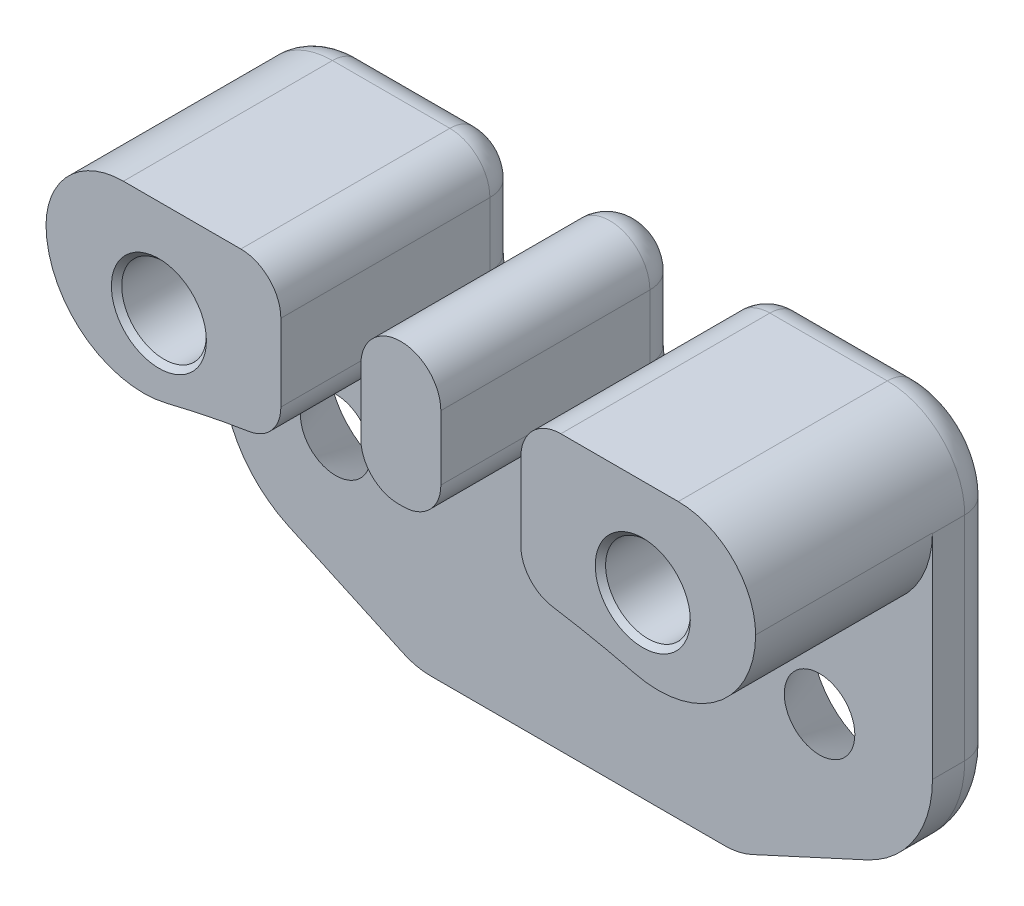
SolidWorks part; units mm, degrees
material "6061-T6 (SS)"
ref_plane "Front" through (0, 0, 0) normal (0, 0, 1) x (1, 0, 0)
ref_plane "Top" through (0, 0, 0) normal (0, 1, 0) x (1, 0, 0)
ref_plane "Right" through (0, 0, 0) normal (1, 0, 0) x (0, 0, -1)
sketch "Sketch1" plane through (0, 0, 0) normal (0, 0, 1) x (1, 0, 0)
  line L1 (0, 0) -> (-69.85, 0)
  line L2 (0, 0) -> (0, 44.45)
  line L3 (0, 44.45) -> (-69.85, 44.45)
  line L4 (-69.85, 0) -> (-69.85, 44.45)
  circle A0 centre (-58.7375, 34.925) radius 4.1672
  circle A1 centre (-11.1125, 34.925) radius 4.1672
  dimension "D3" = 8.3344
  dimension "D1" = 44.45
  dimension "D2" = 69.85
  dimension "D4" = 11.1125
  dimension "D5" = 9.525
  dimension "D6" = 9.525
  dimension "D7" = 11.1125
extrude "Boss-Extrude1" add sketch "Sketch1" against normal blind 23.749
sketch "Sketch2" plane through (0, 0, 0) normal (0, 0, 1) x (1, 0, 0)
  line L0 (-69.85, 0) -> (0, 0) construction
  line L1 (-34.925, 44.45) -> (-34.925, 0) construction
  line L2 (0, 0) -> (0, 44.45) construction
  line L3 (-69.85, 36.9576) -> (-69.85, 0)
  line L4 (-69.85, 0) -> (-34.925, 0)
  line L5 (0, 44.45) -> (-69.85, 44.45) construction
  line L6 (-69.85, 44.45) -> (-69.85, 0) construction
  line L7 (0, 0) -> (0, 36.9576)
  line L8 (-34.925, 0) -> (0, 0)
  arc A0 (-69.85, 36.9576) -> (-57.9471, 27.6559) centre (-60.264, 36.9576) ccw
  arc A1 (-11.9029, 27.6559) -> (-57.9471, 27.6559) centre (-34.925, -64.77) ccw
  arc A2 (0, 36.9576) -> (-11.9029, 27.6559) centre (-9.586, 36.9576) cw
  point P10 (-34.925, 30.48)
  dimension "D2" = 190.5
  dimension "D3" = 19.1719
  dimension "D1" = 13.97
extrude "Cut-Extrude1" cut sketch "Sketch2" against normal blind 17.399
sketch "Sketch3" plane through (0, 0, 0) normal (0, 0, 1) x (1, 0, 0)
  line L3 (-69.85, 36.83) -> (-69.85, 0)
  line L4 (-69.85, 0) -> (0, 0)
  line L5 (0, 0) -> (0, 36.83)
  line L6 (-7.62, 44.45) -> (-62.23, 44.45)
  arc A0 (0, 36.83) -> (-7.62, 44.45) centre (-7.62, 36.83) ccw
  arc A1 (-69.85, 36.83) -> (-62.23, 44.45) centre (-62.23, 36.83) cw
  point P8 (0, 44.45)
  point P11 (-69.85, 44.45)
  dimension "D1" = 7.62
extrude "Cut-Extrude2" cut sketch "Sketch3" against normal up to surface (23.749 mm away) flip side to cut up to face at (-6.9453, 34.925, -23.749)
sketch "Sketch4" plane through (0, 0, -17.399) normal (0, 0, 1) x (1, 0, 0)
  line L0 (-69.85, 44.45) -> (0, 44.45)
  line L1 (-50.8, 0) -> (-19.05, 0)
  line L2 (-69.85, 0) -> (0, 0) construction
  line L3 (-19.05, 0) -> (-6.4739, 5.7769)
  line L5 (-34.925, 44.45) -> (-34.925, 0) construction
  line L6 (0, 44.45) -> (0, 15.875)
  line L8 (-69.85, 44.45) -> (-69.85, 15.875)
  line L9 (-7.62, 44.45) -> (-62.23, 44.45) construction
  line L10 (-69.85, 0) -> (0, 0) construction
  line L11 (-50.8, 0) -> (-63.3761, 5.7769)
  line L12 (-74.8365, 15.875) -> (5.7772, 15.875) construction
  line L13 (-58.7375, 34.925) -> (-58.7375, 15.875) construction
  line L14 (0, 0) -> (0, 36.83) construction
  circle A0 centre (-58.7375, 34.925) radius 4.1672 construction
  arc A1 (0, 15.875) -> (-6.4739, 5.7769) centre (-11.1125, 15.875) cw
  arc A3 (-69.85, 15.875) -> (-63.3761, 5.7769) centre (-58.7375, 15.875) ccw
  dimension "D2" = 15.875
  dimension "D1" = 19.05
extrude "Cut-Extrude3" cut sketch "Sketch4" against normal up to surface (6.35 mm away) flip side to cut up to face at (-6.9453, 34.925, -23.749)
sketch "Sketch5" plane through (0, 0, 0) normal (0, 0, 1) x (1, 0, 0)
  line L1 (-7.62, 44.45) -> (-62.23, 44.45) construction
  line L2 (-38.862, 40.513) -> (-38.862, 34.2208)
  line L3 (-30.988, 34.2208) -> (-30.988, 40.513)
  line L4 (-46.736, 34.2208) -> (-46.736, 40.513)
  line L5 (-50.673, 44.45) -> (-34.925, 44.45)
  line L6 (-23.114, 34.2208) -> (-23.114, 40.513)
  line L7 (-19.177, 44.45) -> (-34.925, 44.45)
  arc A0 (-30.988, 40.513) -> (-38.862, 40.513) centre (-34.925, 40.513) ccw
  arc A1 (-30.988, 34.2208) -> (-23.114, 34.2208) centre (-27.051, 34.2208) ccw
  arc A2 (-46.736, 34.2208) -> (-38.862, 34.2208) centre (-42.799, 34.2208) ccw
  arc A3 (-46.736, 40.513) -> (-50.673, 44.45) centre (-50.673, 40.513) ccw
  arc A4 (-19.177, 44.45) -> (-23.114, 40.513) centre (-19.177, 40.513) ccw
  line M2 (-7.62, 44.45) -> (-62.23, 44.45)
  dimension "D1" = 7.874
extrude "Cut-Extrude4" cut sketch "Sketch5" against normal through all contours A3 L4 A2 L2 A0 M2 | A4 A0 L3 A1 L6 M2
sketch "Sketch6" plane through (0, 0, -23.749) normal (0, 0, -1) x (-1, 0, 0)
  circle A0 centre (11.1125, 15.875) radius 7.1374
  circle A1 centre (58.7375, 15.875) radius 7.1374
  dimension "D1" = 14.2748
  dimension "D2" = 19.05
extrude "Cut-Extrude6" cut sketch "Sketch6" against normal up to next (6.35 mm away) draft 30
sketch "Sketch7" plane through (0, 0, -17.399) normal (0, 0, 1) x (1, 0, 0)
  line L0 (-46.736, 37.3669) -> (-46.736, 27.7882)
  line L1 (-46.736, 34.2208) -> (-46.736, 40.513) construction
  line L2 (-46.736, 37.3669) -> (-38.862, 37.3669)
  line L3 (-38.862, 40.513) -> (-38.862, 34.2208) construction
  line L4 (-38.862, 37.3669) -> (-38.862, 27.7882)
  line L5 (-38.862, 27.7882) -> (-46.736, 27.7882)
  line L6 (-34.925, 44.45) -> (-34.925, 22.2992) construction
  line L7 (-30.988, 27.7882) -> (-23.114, 27.7882)
  line L8 (-30.988, 37.3669) -> (-30.988, 27.7882)
  line L9 (-23.114, 37.3669) -> (-30.988, 37.3669)
  line L10 (-23.114, 37.3669) -> (-23.114, 27.7882)
  arc A0 (-30.988, 40.513) -> (-38.862, 40.513) centre (-34.925, 40.513) ccw construction
extrude "Cut-Extrude7" cut sketch "Sketch7" along normal through all
fillet "Fillet2" radius 3.683 4 edges at (-30.988, 30.3986, -8.6995) (-38.862, 30.3986, -8.6995) (-23.114, 29.7449, -8.6995) (-46.736, 29.7449, -8.6995)
chamfer "Chamfer1" distance 0.508 angle 45 4 edges at (-54.5703, 34.925, -23.749) (-6.9453, 34.925, -23.749) (-6.9453, 34.925, 0) (-54.5703, 34.925, 0)
fillet "Fillet3" radius 6.35 2 edges at (-50.8, 0, -20.574) (-19.05, 0, -20.574)
fillet "Fillet4" radius 3.175 22 edges at (-1.7574, 9.8775, -23.749) (-12.131, 3.1783, -23.749) (-19.0821, 0.1466, -23.749) (-34.925, 0, -23.749) (-50.7679, 0.1466, -23.749) (-57.719, 3.1783, -23.749) (-68.0926, 9.8775, -23.749) (-69.85, 26.3525, -23.749) (-67.6182, 42.2182, -23.749) (-56.4515, 44.45, -23.749) (-47.8891, 43.2969, -23.749) (-46.736, 37.3669, -23.749) (-42.799, 30.2838, -23.749) (-38.862, 37.3669, -23.749) (-34.925, 44.45, -23.749) (-30.988, 37.3669, -23.749) (-27.051, 30.2838, -23.749) (-23.114, 37.3669, -23.749) (-21.9609, 43.2969, -23.749) (-13.3985, 44.45, -23.749) (-2.2318, 42.2182, -23.749) (0, 26.3525, -23.749)
equation "\"D7@Sketch1\" = \"D4@Sketch1\""
equation "\"D6@Sketch1\"= \"D5@Sketch1\""
